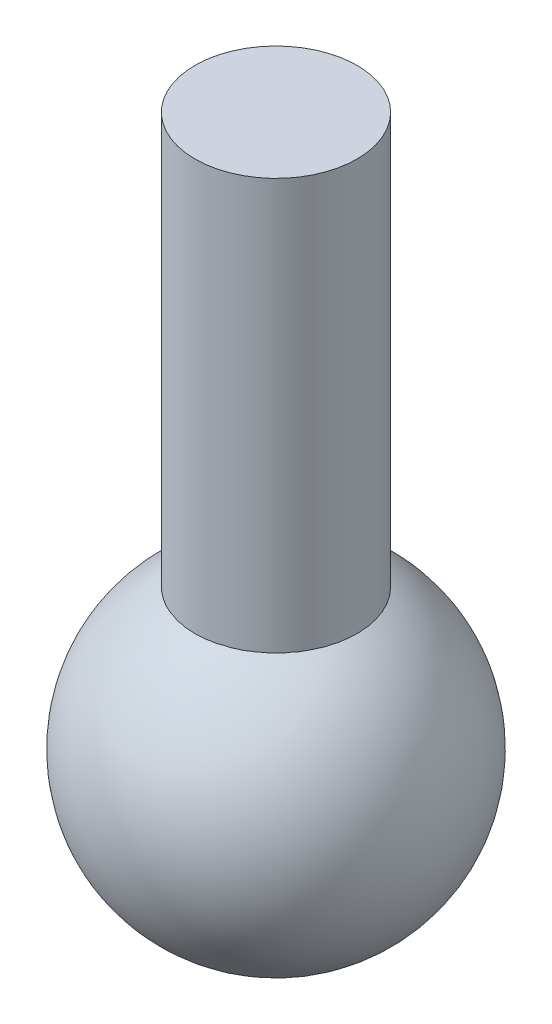
SolidWorks part; units mm, degrees
ref_plane "Front Plane" through (0, 0, 0) normal (0, 0, 1) x (1, 0, 0)
ref_plane "Top Plane" through (0, 0, 0) normal (0, 1, 0) x (1, 0, 0)
ref_plane "Right Plane" through (0, 0, 0) normal (1, 0, 0) x (0, 0, -1)
sketch "Sketch1" plane through (0, 0, 0) normal (0, 1, 0) x (1, 0, 0)
  line L0 (0, 40) -> (0, -30) construction
  line L1 (-11.547, 40) -> (-40.4145, -10)
  line L2 (-28.8675, -30) -> (28.8675, -30)
  line L3 (40.4145, -10) -> (11.547, 40)
  line L4 (11.547, 40) -> (-11.547, 40)
  line L5 (-40.4145, -10) -> (-28.8675, -30)
  line L6 (28.8675, -30) -> (40.4145, -10)
  circle A0 centre (0, 0) radius 30 construction
  circle A1 centre (0, 0) radius 40 construction
  dimension "D2" = 40
  dimension "D1" = 30
  dimension "D3" = 50
extrude "Boss-Extrude1" add sketch "Sketch1" along normal blind 8 contours L4 L1 L5 L2 L6 L3
sketch "Sketch2" plane through (0, 8, 0) normal (0, 1, 0) x (1, 0, 0)
  line L0 (0, 40) -> (0, -30) construction
  line L1 (11.547, 40) -> (-11.547, 40) construction
  line L2 (-28.8675, -30) -> (28.8675, -30) construction
  circle A0 centre (0, 0) radius 5
  dimension "D1" = 10
extrude "Cut-Extrude1" cut sketch "Sketch2" against normal blind 107
pattern_circular "CirPattern1" count 3 over 360 about axis through (0, 0, 0) along (0, 1, 0) of bodies 102 104
sketch "Sketch6" plane through (0, 8, 0) normal (0, 1, 0) x (1, 0, 0)
  circle A0 centre (0, 0) radius 5
extrude "Boss-Extrude3" add sketch "Sketch6" against normal blind 34
sketch "Sketch8" plane through (0, -26, 0) normal (0, -1, 0) x (-1, 0, 0)
  line L0 (0, 0) -> (0, 50000) construction
  line L1 (0, 10) -> (0, -10)
  arc A0 (0, -10) -> (0, 10) centre (0, 0) ccw
  dimension "D1" = 20
revolve "Revolve1" add sketch "Sketch8" angle 360 about L0
sketch "Sketch9" plane through (0, 0, 0) normal (0, -1, 0) x (1, 0, 0)
  circle A0 centre (0, 0) radius 54.2209
  circle A2 centre (0, 0) radius 5
extrude "Cut-Extrude2" cut sketch "Sketch9" against normal blind 10
